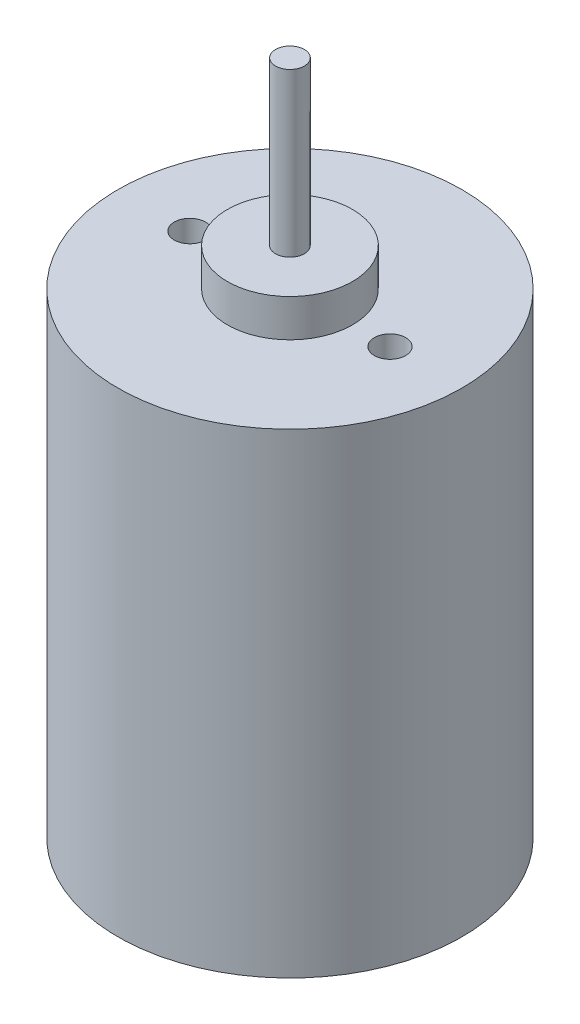
SolidWorks part; units mm, degrees
ref_plane "Front Plane" through (0, 0, 0) normal (0, 0, 1) x (1, 0, 0)
ref_plane "Top Plane" through (0, 0, 0) normal (0, 1, 0) x (1, 0, 0)
ref_plane "Right Plane" through (0, 0, 0) normal (1, 0, 0) x (0, 0, -1)
sketch "Sketch1" plane through (0, 0, 0) normal (1, 0, 0) x (0, 0, -1)
  line L0 (0, 0) -> (0, 57) construction
  line L1 (0, 57) -> (-1.15, 57)
  line L2 (-1.15, 57) -> (-1.15, 44)
  line L3 (-1.15, 44) -> (-5, 44)
  line L4 (-5, 44) -> (-5, 41)
  line L5 (-5, 41) -> (-13.75, 41)
  line L6 (-13.75, 41) -> (-13.75, 3)
  line L7 (-13.75, 3) -> (-5, 3)
  line L8 (-5, 3) -> (-5, 0)
  line L9 (-5, 0) -> (0, 0)
  line L10 (0, 0) -> (0, 57)
  dimension "D1" = 13.75
  dimension "D2" = 1.15
  dimension "D3" = 5
  dimension "D4" = 3
  dimension "D5" = 13
  dimension "D6" = 38
revolve "Revolve1" add sketch "Sketch1" angle 360 about L0
sketch "Sketch2" plane through (0, 41, 0) normal (0, 1, 0) x (1, 0, 0)
  line L0 (-8, 0) -> (0, 0) construction
  circle A0 centre (-8, 0) radius 1.25
  circle A1 centre (8, 0) radius 1.25
  point P2 (2.7193, -4.872)
  point P5 (0, 0)
  point P8 (0, 0)
  point P10 (0, 0)
  dimension "D1" = 2.5
  dimension "D2" = 8
  dimension "D3" = 2
extrude "Cut-Extrude1" cut sketch "Sketch2" against normal blind 10
